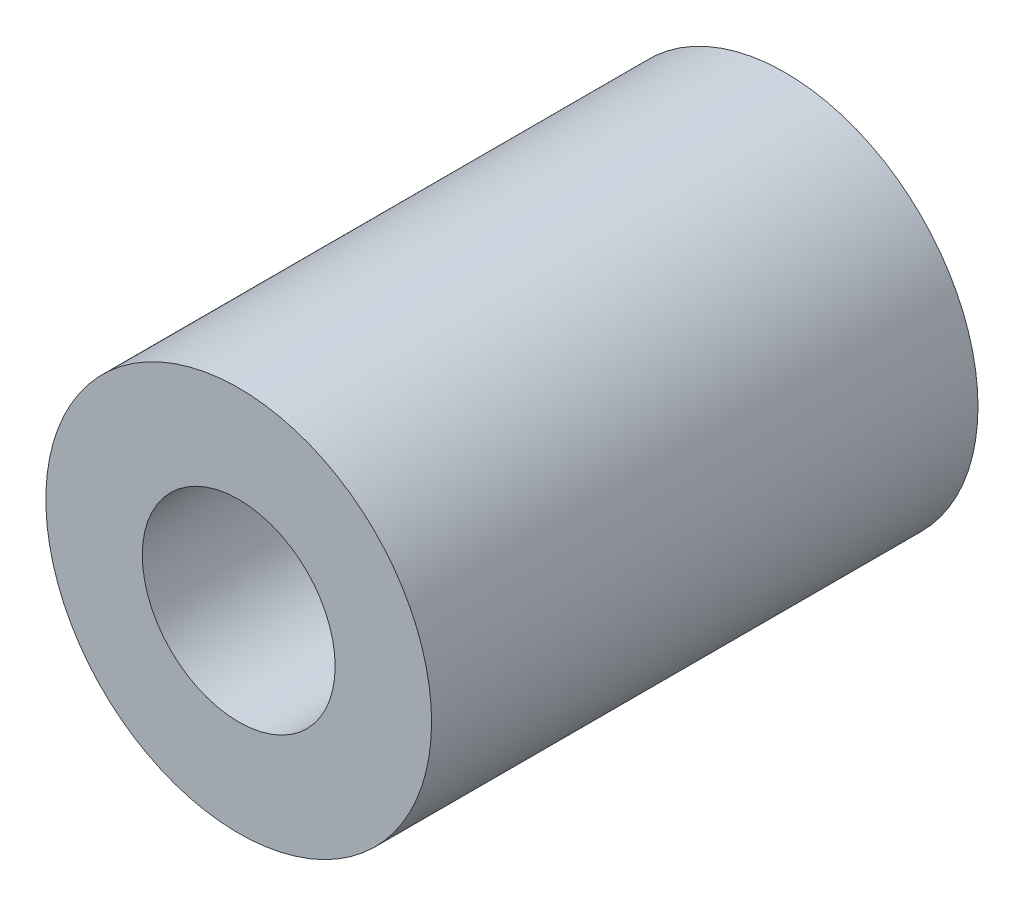
SolidWorks part; units mm, degrees
ref_plane "정면" through (0, 0, 0) normal (0, 0, 1) x (1, 0, 0)
ref_plane "윗면" through (0, 0, 0) normal (0, 1, 0) x (1, 0, 0)
ref_plane "우측면" through (0, 0, 0) normal (1, 0, 0) x (0, 0, -1)
sketch "스케치1" plane through (0, 0, 0) normal (0, 0, 1) x (1, 0, 0)
  circle A0 centre (0, 0) radius 6
  circle A1 centre (0, 0) radius 3
  dimension "D1" = 6
  dimension "D2" = 12
extrude "보스-돌출1" add sketch "스케치1" along normal blind 17
